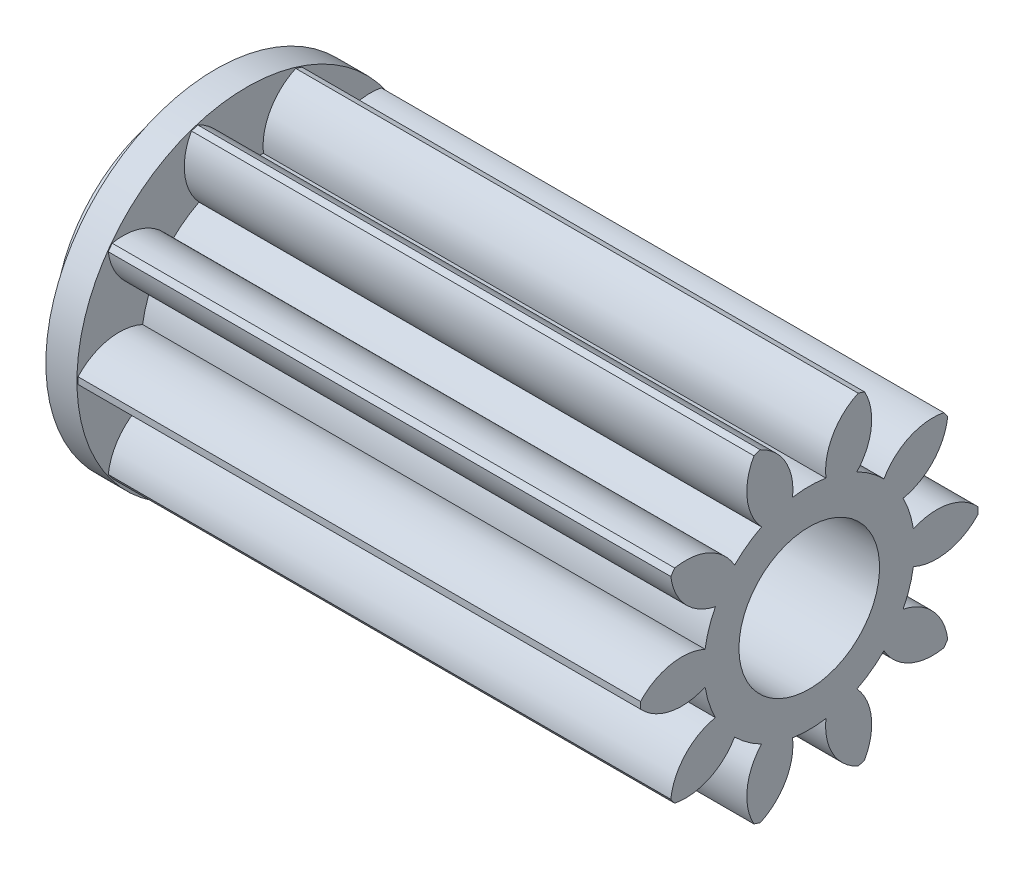
SolidWorks part; units mm, degrees
ref_plane "Plane1" through (0, 0, 0) normal (0, 0, 1) x (1, 0, 0)
ref_plane "Plane2" through (0, 0, 0) normal (0, 1, 0) x (1, 0, 0)
ref_plane "Plane3" through (0, 0, 0) normal (1, 0, 0) x (0, 0, -1)
sketch "HoldingSke" plane through (0, 0, 0) normal (0, 1, 0) x (1, 0, 0)
  line L0 (0, 0) -> (0.9848, -0.1736)
  line L1 (-15, 0) -> (100, 0) construction
  line L2 (0, 0) -> (-2.1039, 2.3779)
  line L3 (0, 0) -> (-11.863, 4.5341)
  line L4 (0, 0) -> (8.5048, 1.4996)
  line L5 (0, 0) -> (-46.8476, -17.4728)
  line L6 (0, 0) -> (-16.5793, -11.1861)
  line L7 (-2.1039, 2.3779) -> (8.6586, 51.2059)
  line L8 (-76.2, 54.61) -> (-75.3, 54.61)
  line L9 (-71.009, 38.7566) -> (-53.1078, 45.2721)
  line L10 (-76.2, 71.12) -> (104.1128, 71.12)
  line L11 (0, 0) -> (-20, 0)
  line L12 (-76.2, 101.6) -> (-76.162, 101.6)
  line L13 (24.9733, 27.94) -> (52.9518, 28.4284)
  line L14 (24.9733, 27.94) -> (24.9743, 27.94)
  line L15 (24.9733, 27.94) -> (100.4006, 29.5858)
  line L16 (-63.627, -1) -> (-12.827, -1)
  circle A0 centre (0, 0) radius 2.5
  circle A1 centre (0, 0) radius 3.749
  circle A2 centre (0, 0) radius 37.5
  circle A3 centre (0, 0) radius 2.5
  dimension "MHD" = 7.498
  dimension "Hub_dia" = 75
  dimension "Bore" = 5
  dimension "MBD" = 5
  dimension "Num_teeth" = 10
  dimension "Pitch" = 1
  dimension "Overall_len" = 50
  dimension "Show_teeth" = 10
  dimension "Thickness" = 20
  dimension "OAL" = 50.0001
  dimension "T_dim" = 0.9
  dimension "Ap" = 20
  dimension "H" = 19.05
  dimension "Pitch_radius" = 180.3128
  dimension "Width" = 20
  dimension "Backlash" = 0.038
  dimension "Addendum_fac" = 1
  dimension "Dedendum_fac" = 1.25
  dimension "Clearance_fac" = 0.25
  dimension "Dedendum_add" = 0.001
  dimension "Module" = 1
sketch "BasProSke" plane through (0, 0, 0) normal (0, 1, 0) x (1, 0, 0)
  line L0 (-10, 0) -> (60, 0) construction
  line L1 (0, 0) -> (0, 6)
  line L2 (0, 0) -> (20, 0)
  line L3 (20, 0) -> (20, 6)
  line L4 (20, 6) -> (0, 6)
  dimension "Thickness" = 20
  dimension "Diameter" = 12
revolve "Base-Revolve" add sketch "BasProSke" angle 360 about L0
sketch "TooCutSke" plane through (0, 0, 0) normal (1, 0, 0) x (0, 0, -1)
  line L1 (0, 0) -> (0, 107) construction
  line L2 (0, 0) -> (-0.8485, 4.9275) construction
  line L3 (0, 0) -> (-3.0584, 9.4126) construction
  line L4 (-0.8485, 4.9275) -> (-1.5292, 4.7063) construction
  arc A0 (0.5928, 3.7018) -> (-0.5928, 3.7018) centre (0, 0) ccw
  arc A1 (1.7758, 5.7578) -> (-1.7758, 5.7578) centre (0, 0) ccw
  circle A2 centre (0, 0) radius 5 construction
  circle A3 centre (0, 0) radius 4.6985 construction
  arc A4 (-0.5928, 3.7018) -> (-1.7758, 5.7578) centre (-2.5801, 3.9267) ccw
  arc A5 (1.7758, 5.7578) -> (0.5928, 3.7018) centre (2.5801, 3.9267) ccw
  dimension "Root_dia" = 7.498
  dimension "Overcut_dia" = 12.0508
  dimension "Pitch_dia" = 10
  dimension "Base_dia" = 9.3969
  dimension "Flank_rad" = 2
  dimension "Half_ang" = 18
  dimension "Half_CT" = 0.7157
extrude "ToothCut" cut sketch "TooCutSke" along normal through all
fillet "Breaks" [suppressed] radius 0.02
fillet "RootFillets" [suppressed] radius 0.251
pattern_circular "TeethCuts" count 10 every 36 about axis through (-10, 0, 0) along (1, 0, 0) of "ToothCut", "RootFillets", "Breaks"
sketch "HubNeaOneSke" plane through (0, 0, 0) normal (-1, 0, 0) x (0, 0, 1)
  circle A0 centre (0, 0) radius 3.749
  dimension "Diameter" = 7.498
extrude "HubNearOne" [suppressed] add sketch "HubNeaOneSke" along normal blind 30.0001
sketch "HubNeaBotSke" plane through (0, 0, 0) normal (-1, 0, 0) x (0, 0, 1)
  circle A0 centre (0, 0) radius 3.749
  dimension "Diameter" = 7.498
extrude "HubNearBoth" [suppressed] add sketch "HubNeaBotSke" along normal blind 15
ref_plane "FarPln" through (20, 0, 0) normal (1, 0, 0) x (0, 0, -1)
sketch "HubFarSke" plane through (20, 0, 0) normal (1, 0, 0) x (0, 0, -1)
  circle A0 centre (0, 0) radius 3.749
  dimension "Diameter" = 7.498
extrude "HubFar" [suppressed] add sketch "HubFarSke" along normal blind 15
sketch "BorSke" plane through (0, 0, 0) normal (1, 0, 0) x (0, 0, -1)
  circle A0 centre (0, 0) radius 2.5
  dimension "Diameter" = 5
extrude "Bore" cut sketch "BorSke" along normal mid plane 100.0001
sketch "KeySke" plane through (0, 0, 0) normal (1, 0, 0) x (0, 0, -1)
  line L0 (-1, 0) -> (-1, 3.4)
  line L1 (-1, 3.4) -> (1, 3.4)
  line L2 (1, 3.4) -> (1, 0)
  line L3 (0, 0) -> (0, 34) construction
  line L4 (-1, 0) -> (1, 0)
  dimension "Offset" = 3.4
extrude "Keyway" [suppressed] cut sketch "KeySke" along normal mid plane 100.0001
pattern_circular "Keyway2" [suppressed] count 2 every 90 about axis through (-10, 0, 0) along (1, 0, 0)
scale "Масштаб1" scale about centroid uniform scaling yes scale factor 1.085
sketch "Эскиз2" plane through (0, 0, 0) normal (0, 1, 0) x (1, 0, 0)
  line L0 (0, 0) -> (-5.94, 0) construction
  line L1 (-0.85, 5.1898) -> (-0.85, 2.8812) construction
  line L2 (-0.85, 3.5) -> (-0.85, 6.55)
  line L3 (-0.85, 6.55) -> (-2.05, 6.55)
  line L4 (-2.05, 6.55) -> (-2.05, 5)
  line L5 (-2.05, 5) -> (-3.25, 5)
  line L6 (-3.25, 5) -> (-3.25, 3.9243)
  line L7 (-3.25, 3.9243) -> (-2.8257, 3.5)
  line L8 (-2.8257, 3.5) -> (-0.85, 3.5)
  point P7 (0, 3.5)
  point P11 (0, 0)
  point P12 (-0.85, 3.5)
  dimension "D1" = 7
  dimension "D2" = 13.1
  dimension "D3" = 1.2
  dimension "D4" = 1.2
  dimension "D5" = 10
  dimension "D6" = 45
  dimension "D7" = 0.6
revolve "Повернуть1" add sketch "Эскиз2" angle 360 about L0
equation "' \"Module@HoldingSke\" = 6.35"
equation "' \"Num_teeth@HoldingSke\" = 12"
equation "' \"Ap@HoldingSke\" =  20"
equation "' \"Ap@HoldingSke\" = 20"
equation "' \"Width@HoldingSke\" = 0.5 * 25.4"
equation "' \"Hub_dia@HoldingSke\"= 1 * 25.4"
equation "' \"Hub_dia@HoldingSke\" = 1 * 25.4"
equation "' \"Overall_len@HoldingSke\" = 1.0 * 25.4"
equation "' \"Bore@HoldingSke\" = 0.75 * 25.4"
equation "' \"T_dim@HoldingSke\" = 0.1 * 25.4"
equation "' \"Width@KeySke\" = 0.25 * 25.4"
equation "' \"Show_teeth@HoldingSke\" = 13"
equation "' \"Backlash@HoldingSke\" = 0.009 * 25.4"
equation "' \"Addendum_fac@HoldingSke\" = 1.0"
equation "' \"Dedendum_fac@HoldingSke\" = 1.25"
equation "' \"Dedendum_add@HoldingSke\" = 0.00005 * 25.4"
equation "' \"Clearance_fac@HoldingSke\" = 0.25"
equation "\"Pitch@HoldingSke\" = 1 / \"Module@HoldingSke\""
equation "\"Overcut_dia@TooCutSke\" = (\"Num_teeth@HoldingSke\" + 2 * \"Addendum_fac@HoldingSke\") / \"Pitch@HoldingSke\" + 0.002 * 25.4"
equation "\"Pitch_dia@TooCutSke\" = \"Num_teeth@HoldingSke\" / \"Pitch@HoldingSke\""
equation "\"Base_dia@TooCutSke\" = \"Num_teeth@HoldingSke\" / \"Pitch@HoldingSke\" * cos((\"Ap@HoldingSke\"  * 3.14159265 / 180))"
equation "\"Root_dia@TooCutSke\" = (\"Num_teeth@HoldingSke\" + 2) / \"Pitch@HoldingSke\" - 2 * (\"Addendum_fac@HoldingSke\" + \"Dedendum_fac@HoldingSke\") / \"Pitch@HoldingSke\" - \"Dedendum_add@HoldingSke\" * 2"
equation "\"Half_ang@TooCutSke\" = 180 / \"Num_teeth@HoldingSke\""
equation "\"Half_CT@TooCutSke\" = \"Num_teeth@HoldingSke\" / \"Pitch@HoldingSke\" * sin((3.14159265 / 2 / \"Num_teeth@HoldingSke\")) / 2 - 7 * \"Backlash@HoldingSke\" / 4"
equation "\"Flank_rad@TooCutSke\" = \"Num_teeth@HoldingSke\" / \"Pitch@HoldingSke\" / 5"
equation "\"Radius@RootFillets\" = \"Clearance_fac@HoldingSke\" / \"Pitch@HoldingSke\" + \"Dedendum_add@HoldingSke\""
equation "\"Break_rad@Breaks\" = 0.02 / \"Pitch@HoldingSke\""
equation "\"Thickness@HoldingSke\" = \"Width@HoldingSke\""
equation "\"OAL@HoldingSke\" = \"Thickness@HoldingSke\""
equation "\"MHD@HoldingSke\" = (\"Num_teeth@HoldingSke\" + 2) / \"Pitch@HoldingSke\" - 2 * (\"Addendum_fac@HoldingSke\" + \"Dedendum_fac@HoldingSke\")  / \"Pitch@HoldingSke\" - \"Dedendum_add@HoldingSke\" * 2"
equation "\"MBD@HoldingSke\" = (\"Num_teeth@HoldingSke\" + 2) / \"Pitch@HoldingSke\" - 2 * (\"Addendum_fac@HoldingSke\" + \"Dedendum_fac@HoldingSke\")  / \"Pitch@HoldingSke\" - \"Dedendum_add@HoldingSke\" * 2 - 0.002 * 25.4"
equation "\"MHD@HoldingSke\" = ((sgn( \"MHD@HoldingSke\" - \"Hub_dia@HoldingSke\" )-1)*( \"MHD@HoldingSke\" - \"Hub_dia@HoldingSke\" ))/-2+ \"Hub_dia@HoldingSke\""
equation "\"MBD@HoldingSke\" = ((sgn( \"MBD@HoldingSke\" - \"Bore@HoldingSke\" )-1)*( \"MBD@HoldingSke\" - \"Bore@HoldingSke\" ))/-2+ \"Bore@HoldingSke\""
equation "\"OAL@HoldingSke\" = ((sgn( \"OAL@HoldingSke\" - \"Overall_len@HoldingSke\" )+1)*( \"OAL@HoldingSke\" - \"Overall_len@HoldingSke\" ))/2 + \"Overall_len@HoldingSke\" + 0.000002 * 25.4"
equation "\"Num_teeth@TeethCuts\" = int( \"Show_teeth@HoldingSke\" ) + 1"
equation "\"Num_teeth@TeethCuts\" = ((sgn( \"Num_teeth@TeethCuts\" - \"Num_teeth@HoldingSke\" )-1)*( \"Num_teeth@TeethCuts\" - \"Num_teeth@HoldingSke\" ))/-2+ \"Num_teeth@HoldingSke\""
equation "\"Num_teeth@TeethCuts\" = ((sgn( \"Num_teeth@TeethCuts\" - 2.0)+1)*( \"Num_teeth@TeethCuts\" - 2.0))/2 +2.0"
equation "\"Angle@TeethCuts\" = 360.0 / \"Num_teeth@HoldingSke\""
equation "\"Diameter@BasProSke\" = (\"Num_teeth@HoldingSke\" + 2 * \"Addendum_fac@HoldingSke\") / \"Pitch@HoldingSke\""
equation "\"Thickness@BasProSke\"  = \"Thickness@HoldingSke\""
equation "' \"Fillet_rad@BasProSke\" =  \"Thickness@HoldingSke\" * 0.05"
equation "' \"Fillet_rad@BasProSke\" = \"Thickness@HoldingSke\" * 0.05"
equation "\"MHD@HoldingSke\" = ((sgn( \"MHD@HoldingSke\" - \"Root_dia@TooCutSke\" )-1)*( \"MHD@HoldingSke\" - \"Root_dia@TooCutSke\" ))/-2+ \"Root_dia@TooCutSke\""
equation "\"Diameter@HubNeaOneSke\" = \"MHD@HoldingSke\""
equation "\"Length@HubNearOne\" = \"OAL@HoldingSke\" - \"Thickness@BasProSke\""
equation "\"Diameter@HubNeaBotSke\" = \"MHD@HoldingSke\""
equation "\"Length@HubNearBoth\" = ( \"OAL@HoldingSke\" - \"Thickness@BasProSke\" ) / 2.0"
equation "\"Thickness@FarPln\" = \"Thickness@BasProSke\""
equation "\"Diameter@HubFarSke\" = \"MHD@HoldingSke\""
equation "\"Length@HubFar\" = ( \"OAL@HoldingSke\" - \"Thickness@BasProSke\" ) / 2.0"
equation "\"Diameter@BorSke\" = \"MBD@HoldingSke\""
equation "\"D1@Bore\" = \"OAL@HoldingSke\" * 2.0"
equation "\"D1@Keyway\" = \"OAL@HoldingSke\" * 2.0"
equation "\"Offset@KeySke\" = \"T_dim@HoldingSke\" + \"MBD@HoldingSke\" / 2.0"
